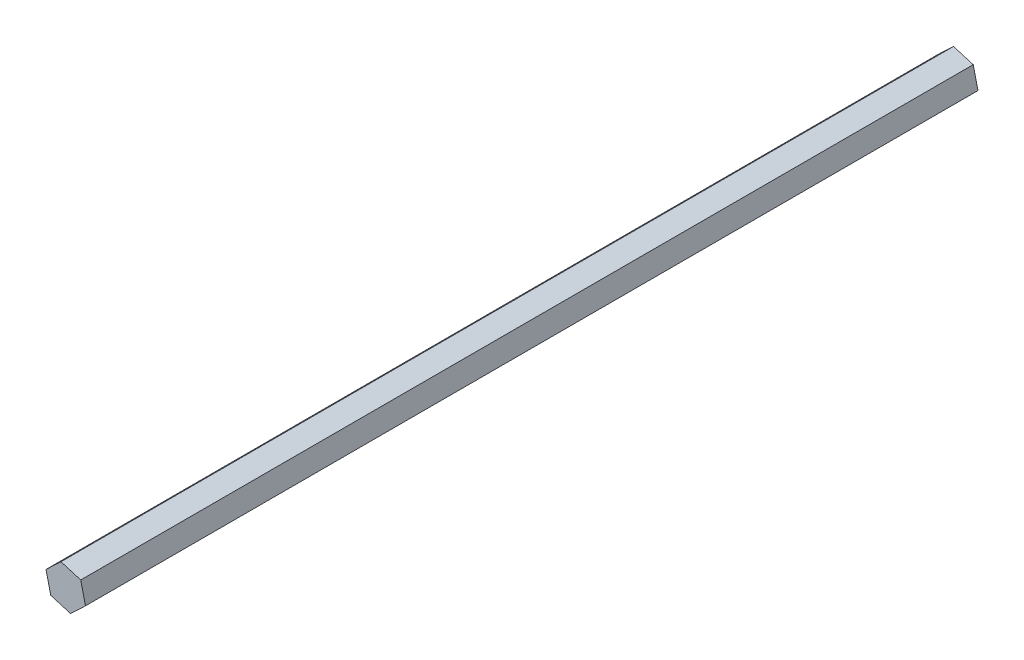
SolidWorks part; units mm, degrees
ref_plane "Front Plane" through (0, 0, 0) normal (0, 0, 1) x (1, 0, 0)
ref_plane "Top Plane" through (0, 0, 0) normal (0, 1, 0) x (1, 0, 0)
ref_plane "Right Plane" through (0, 0, 0) normal (1, 0, 0) x (0, 0, -1)
sketch "Sketch1" plane through (0, 0, 0) normal (0, 0, 1) x (1, 0, 0)
  line L1 (5.3307, 5.0346) -> (-1.6947, 7.1338)
  line L2 (-1.6947, 7.1338) -> (-7.0254, 2.0993)
  line L3 (-7.0254, 2.0993) -> (-5.3307, -5.0346)
  line L4 (-5.3307, -5.0346) -> (1.6947, -7.1338)
  line L5 (1.6947, -7.1338) -> (7.0254, -2.0993)
  line L6 (7.0254, -2.0993) -> (5.3307, 5.0346)
  circle A0 centre (0, 0) radius 6.35 construction
  dimension "D1" = 12.7
extrude "Boss-Extrude1" add sketch "Sketch1" along normal blind 317.5
